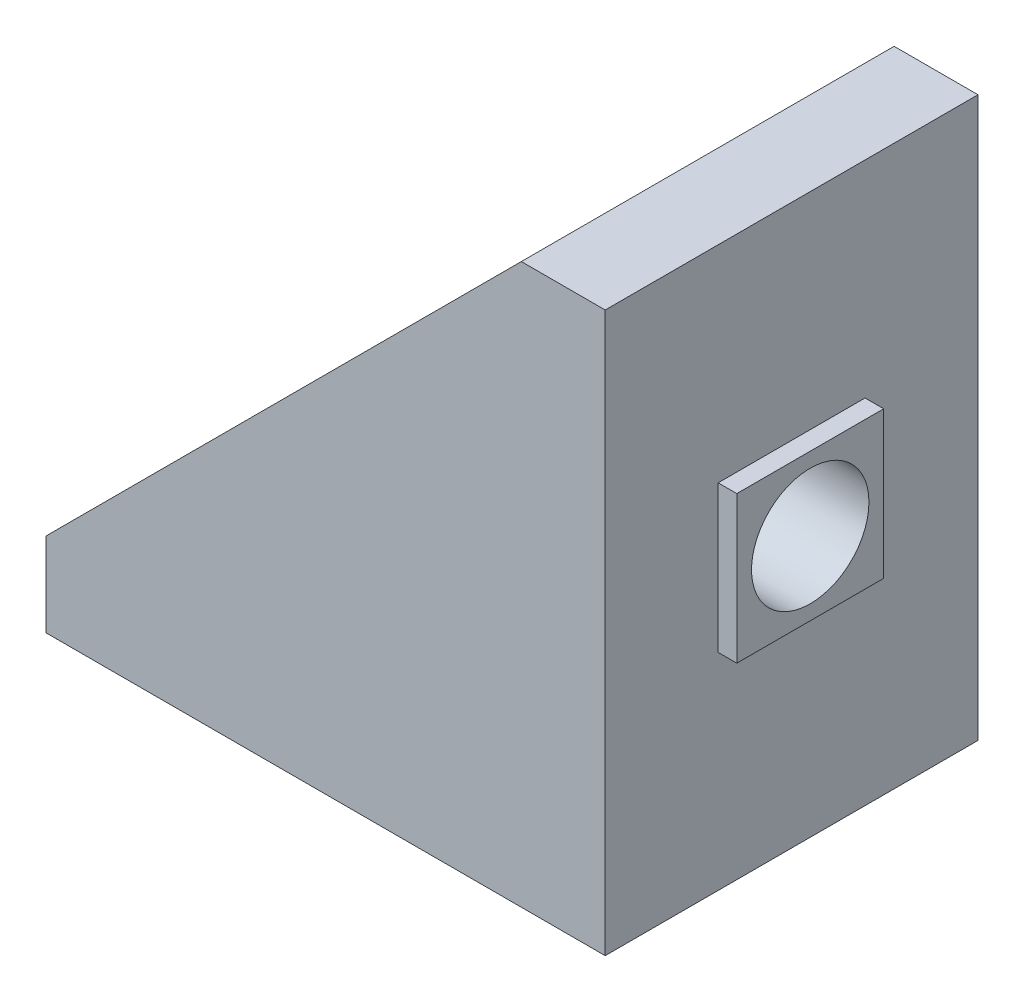
SolidWorks part; units mm, degrees
ref_plane "Front Plane" through (0, 0, 0) normal (0, 0, 1) x (1, 0, 0)
ref_plane "Top Plane" through (0, 0, 0) normal (0, 1, 0) x (1, 0, 0)
ref_plane "Right Plane" through (0, 0, 0) normal (1, 0, 0) x (0, 0, -1)
sketch "Sketch1" plane through (0, 0, 0) normal (0, 0, 1) x (1, 0, 0)
  line L0 (0, 0) -> (0, 30)
  line L1 (0, 30) -> (-4.5, 30)
  line L2 (-4.5, 30) -> (-30, 4.5)
  line L3 (-30, 4.5) -> (-30, 0)
  line L4 (-30, 0) -> (0, 0)
  dimension "D1" = 30
  dimension "D2" = 4.5
extrude "Boss-Extrude1" add sketch "Sketch1" along normal blind 20 contours L2 L3 L4 L0 L1
sketch "Sketch2" plane through (0, 0, 20) normal (0, 0, 1) x (1, 0, 0)
  line L0 (-30, 4.5) -> (-4.5, 4.5)
  line L1 (-4.5, 4.5) -> (-4.5, 30)
  line L2 (-30, 4.5) -> (-4.5, 30)
extrude "Cut-Extrude1" cut sketch "Sketch2" against normal offset from surface (16 mm away) 2 from offset 2 up to face at (-12.9, 12.9, 0) offset against normal yes
sketch "Sketch3" plane through (0, 0, 0) normal (1, 0, 0) x (0, 0, -1)
  line L0 (-20, 30) -> (0, 30) construction
  line L1 (-13.94, 18.94) -> (-6.06, 18.94)
  line L2 (-13.94, 18.94) -> (-13.94, 11.06)
  line L3 (-13.94, 11.06) -> (-6.06, 11.06)
  line L4 (-6.06, 18.94) -> (-6.06, 11.06)
  line L5 (-13.94, 18.94) -> (-6.06, 11.06) construction
  line L6 (-13.94, 11.06) -> (-6.06, 18.94) construction
  line L7 (-20, 0) -> (-20, 30) construction
  point P0 (-10, 15)
  point P9 (-14.3095, 8.4021)
  dimension "D1" = 7.88
  dimension "D2" = 15
  dimension "D3" = 10
extrude "Boss-Extrude2" add sketch "Sketch3" along normal blind 1
sketch "Sketch4" plane through (1, 0, 0) normal (1, 0, 0) x (0, 0, -1)
  line L0 (-10, 18.94) -> (-10, 11.06) construction
  line L1 (-6.06, 18.94) -> (-13.94, 18.94) construction
  line L2 (-13.94, 11.06) -> (-6.06, 11.06) construction
  circle A0 centre (-10, 15) radius 3.15
  dimension "D1" = 6.3
extrude "Cut-Extrude2" cut sketch "Sketch4" against normal through all
sketch "Sketch5" plane through (0, 0, 0) normal (0, -1, 0) x (1, 0, 0)
  line L0 (0, 10) -> (-30, 10) construction
  line L1 (-23.8, 13.85) -> (-25.8, 13.85)
  line L2 (-23.8, 13.85) -> (-23.8, 6.15)
  line L3 (-23.8, 6.15) -> (-25.8, 6.15)
  line L4 (-25.8, 13.85) -> (-25.8, 6.15)
  line L5 (-23.8, 13.85) -> (-25.8, 6.15) construction
  line L6 (-23.8, 6.15) -> (-25.8, 13.85) construction
  line L7 (-4.6, 13.85) -> (-9.6, 13.85)
  line L8 (-4.6, 13.85) -> (-4.6, 6.15)
  line L9 (-4.6, 6.15) -> (-9.6, 6.15)
  line L10 (-9.6, 13.85) -> (-9.6, 6.15)
  line L11 (-4.6, 13.85) -> (-9.6, 6.15) construction
  line L12 (-4.6, 6.15) -> (-9.6, 13.85) construction
  line L13 (0, 20) -> (0, 0) construction
  line L14 (-30, 20) -> (-30, 0) construction
  point P0 (-24.8, 10)
  point P5 (-7.1, 10)
  dimension "D1" = 5
  dimension "D2" = 7.7
  dimension "D3" = 2
  dimension "D4" = 9.6
  dimension "D5" = 6.2
extrude "Boss-Extrude3" add sketch "Sketch5" along normal blind 1
sketch "Sketch6" plane through (0, 0, 0) normal (0, -1, 0) x (1, 0, 0)
  line L0 (-18, 10) -> (0, 10) construction
  line L1 (0, 20) -> (0, 0) construction
  circle A0 centre (-18, 10) radius 3.15
  dimension "D2" = 6.3
  dimension "D1" = 18
extrude "Cut-Extrude3" cut sketch "Sketch6" against normal through all
